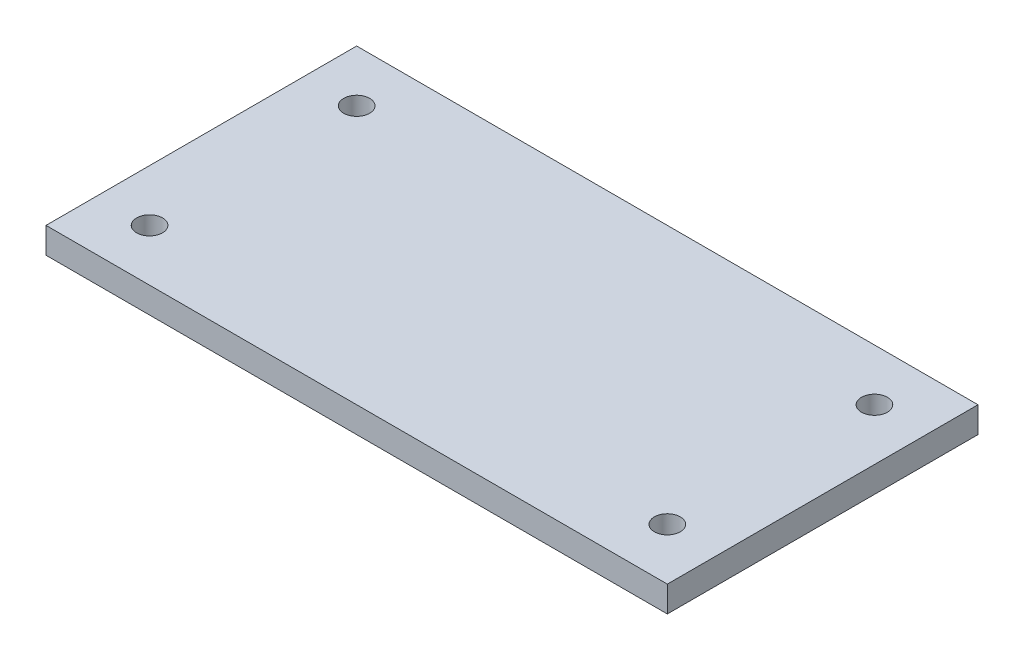
SolidWorks part; units mm, degrees
ref_plane "Front Plane" through (0, 0, 0) normal (0, 0, 1) x (1, 0, 0)
ref_plane "Top Plane" through (0, 0, 0) normal (0, 1, 0) x (1, 0, 0)
ref_plane "Right Plane" through (0, 0, 0) normal (1, 0, 0) x (0, 0, -1)
sketch "Sketch1" plane through (0, 0, 0) normal (0, 1, 0) x (1, 0, 0)
  line L0 (-63.5, -25.4) -> (-63.5, 25.4) construction
  line L1 (-76.2, -38.1) -> (76.2, -38.1)
  line L2 (-76.2, -38.1) -> (-76.2, 38.1)
  line L3 (-76.2, 38.1) -> (76.2, 38.1)
  line L4 (76.2, -38.1) -> (76.2, 38.1)
  line L5 (-76.2, -38.1) -> (76.2, 38.1) construction
  line L6 (-76.2, 38.1) -> (76.2, -38.1) construction
  line L7 (-63.5, 25.4) -> (63.5, 25.4) construction
  line L8 (63.5, -25.4) -> (63.5, 25.4) construction
  line L9 (-63.5, -25.4) -> (63.5, -25.4) construction
  circle A0 centre (-63.5, 25.4) radius 3.1826
  circle A1 centre (63.5, 25.4) radius 3.1826
  circle A2 centre (63.5, -25.4) radius 3.1826
  circle A3 centre (-63.5, -25.4) radius 3.1826
  point P0 (0, 0)
  dimension "D4" = 6.3652
  dimension "D1" = 76.2
  dimension "D2" = 152.4
  dimension "D3" = 12.7
extrude "Boss-Extrude1" add sketch "Sketch1" along normal blind 6.35
